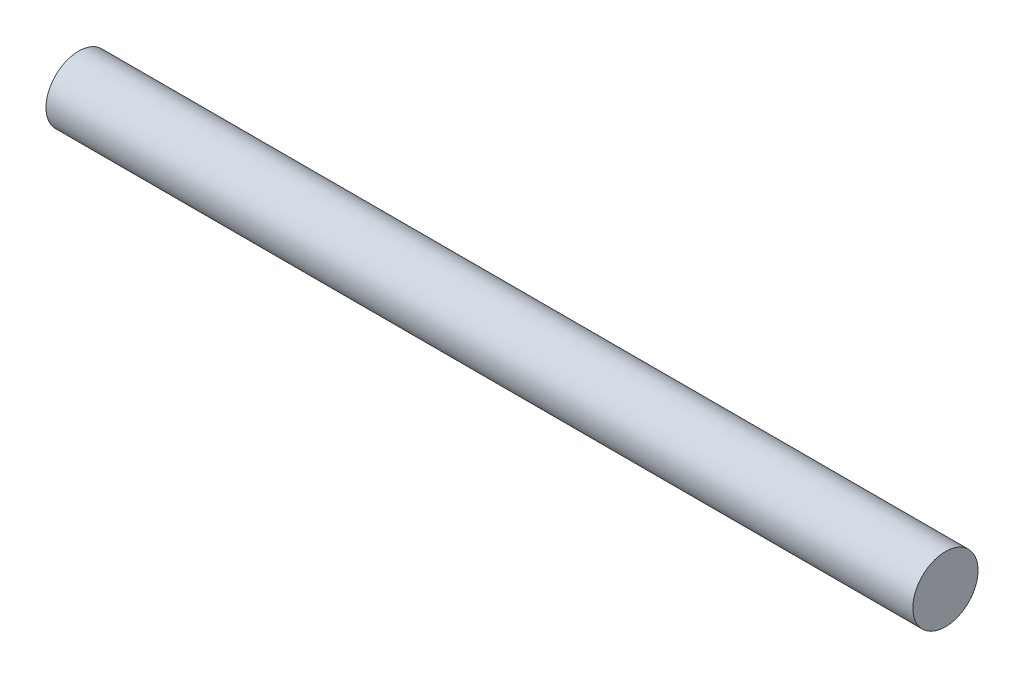
SolidWorks part; units mm, degrees
material "6061 Alloy"
ref_plane "Front Plane" through (0, 0, 0) normal (0, 0, 1) x (1, 0, 0)
ref_plane "Top Plane" through (0, 0, 0) normal (0, 1, 0) x (1, 0, 0)
ref_plane "Right Plane" through (0, 0, 0) normal (1, 0, 0) x (0, 0, -1)
sketch "Sketch1" plane through (0, 0, 0) normal (1, 0, 0) x (0, 0, -1)
  circle A0 centre (0, 0) radius 2.5
  dimension "D1" = 5
extrude "Boss-Extrude1" add sketch "Sketch1" along normal blind 66.4
